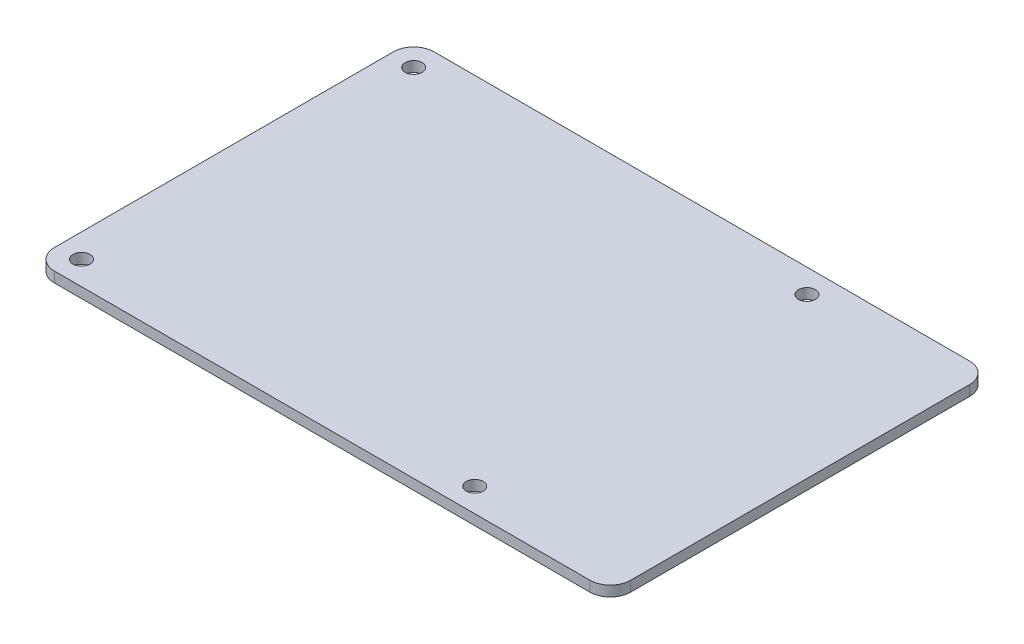
SolidWorks part; units mm, degrees
ref_plane "Front Plane" through (0, 0, 0) normal (0, 0, 1) x (1, 0, 0)
ref_plane "Top Plane" through (0, 0, 0) normal (0, 1, 0) x (1, 0, 0)
ref_plane "Right Plane" through (0, 0, 0) normal (1, 0, 0) x (0, 0, -1)
sketch "Sketch1" plane through (0, 0, 0) normal (0, 1, 0) x (1, 0, 0)
  line L0 (61.5, 3.5) -> (61.5, 0) construction
  line L1 (0, 0) -> (85, 0)
  line L2 (0, 0) -> (0, 56)
  line L3 (0, 56) -> (85, 56)
  line L4 (85, 0) -> (85, 56)
  line L5 (3.5, 52.5) -> (61.5, 52.5) construction
  line L6 (3.5, 52.5) -> (3.5, 3.5) construction
  line L7 (3.5, 3.5) -> (61.5, 3.5) construction
  line L8 (61.5, 52.5) -> (61.5, 3.5) construction
  line L9 (61.5, 52.5) -> (61.5, 56) construction
  circle A0 centre (61.5, 52.5) radius 1.25
  circle A1 centre (61.5, 3.5) radius 1.25
  circle A2 centre (3.5, 3.5) radius 1.25
  circle A3 centre (3.5, 52.5) radius 1.25
  dimension "D5" = 2.5
  dimension "D1" = 56
  dimension "D2" = 85
  dimension "D3" = 58
  dimension "D4" = 49
  dimension "D6" = 3.5
extrude "Boss-Extrude1" add sketch "Sketch1" along normal blind 1.524
fillet "Fillet1" radius 3 4 edges at (0, 0.762, -56) (85, 0.762, -56) (85, 0.762, 0) (0, 0.762, 0)
ref_plane "Plane1" through (0, 0, -28) normal (0, 0, 1) x (1, 0, 0)
ref_plane "Plane2" through (42.5, 0, 0) normal (-1, 0, 0) x (0, 0, 1)
